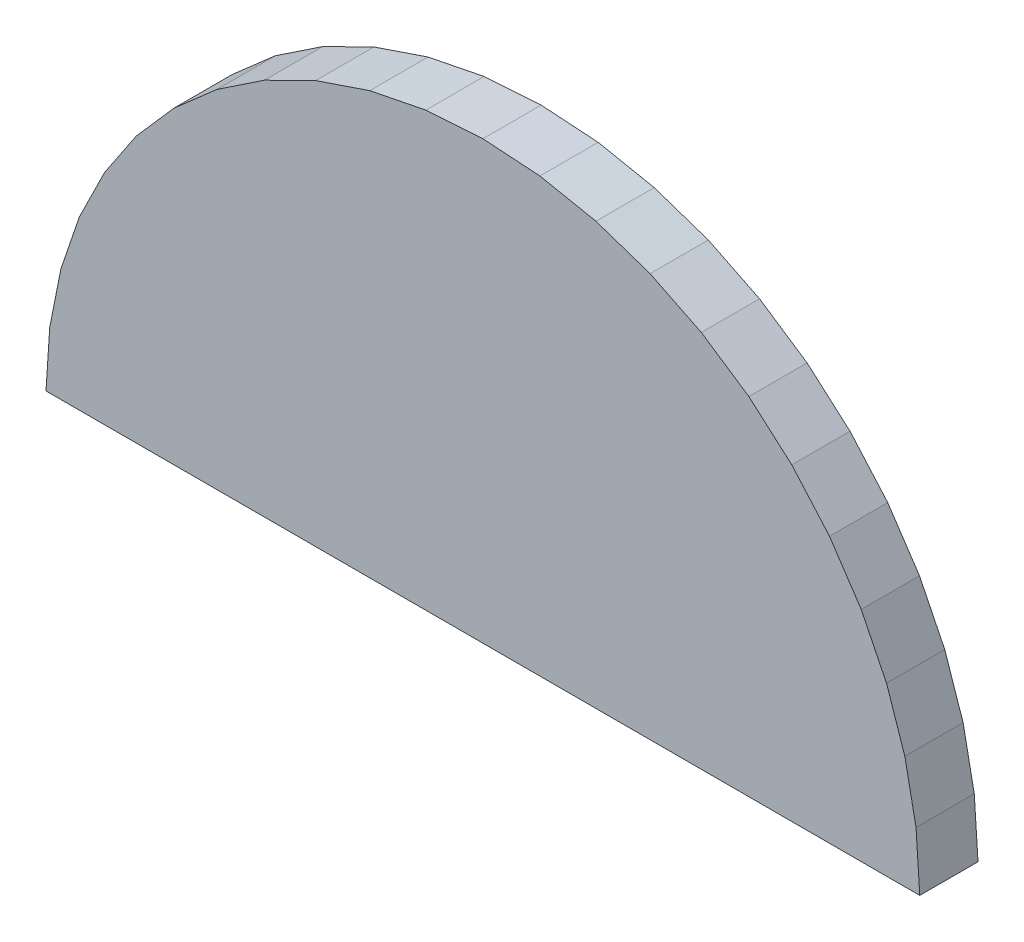
SolidWorks part; units mm, degrees
ref_plane "前视基准面" through (0, 0, 0) normal (0, 0, 1) x (1, 0, 0)
ref_plane "上视基准面" through (0, 0, 0) normal (0, 1, 0) x (1, 0, 0)
ref_plane "右视基准面" through (0, 0, 0) normal (1, 0, 0) x (0, 0, -1)
other "Configuration Table"
sketch "草图1" plane through (0, 0, 0) normal (0, 0, 1) x (1, 0, 0)
  line L0 (90, 0) -> (89.23, 11.7474)
  line L1 (89.23, 11.7474) -> (86.9333, 23.2937)
  line L2 (86.9333, 23.2937) -> (83.1492, 34.4415)
  line L3 (83.1492, 34.4415) -> (77.9423, 45)
  line L4 (77.9423, 45) -> (71.4018, 54.7885)
  line L5 (71.4018, 54.7885) -> (63.6396, 63.6396)
  line L6 (63.6396, 63.6396) -> (54.7885, 71.4018)
  line L7 (54.7885, 71.4018) -> (45, 77.9423)
  line L8 (45, 77.9423) -> (34.4415, 83.1492)
  line L9 (34.4415, 83.1492) -> (23.2937, 86.9333)
  line L10 (23.2937, 86.9333) -> (11.7474, 89.23)
  line L11 (11.7474, 89.23) -> (0, 90)
  line L12 (0, 90) -> (-11.7474, 89.23)
  line L13 (-11.7474, 89.23) -> (-23.2937, 86.9333)
  line L14 (-23.2937, 86.9333) -> (-34.4415, 83.1492)
  line L15 (-34.4415, 83.1492) -> (-45, 77.9423)
  line L16 (-45, 77.9423) -> (-54.7885, 71.4018)
  line L17 (-54.7885, 71.4018) -> (-63.6396, 63.6396)
  line L18 (-63.6396, 63.6396) -> (-71.4018, 54.7885)
  line L19 (-71.4018, 54.7885) -> (-77.9423, 45)
  line L20 (-77.9423, 45) -> (-83.1492, 34.4415)
  line L21 (-83.1492, 34.4415) -> (-86.9333, 23.2937)
  line L22 (-86.9333, 23.2937) -> (-89.23, 11.7474)
  line L23 (-89.23, 11.7474) -> (-90, 0)
  line L24 (-90, 0) -> (90, 0)
  dimension "x0" = 90
  dimension "x1" = 89.23
  dimension "x2" = 86.9333
  dimension "x3" = 83.1492
  dimension "x4" = 77.9423
  dimension "x5" = 71.4018
  dimension "x6" = 63.6396
  dimension "x7" = 54.7885
  dimension "x8" = 45
  dimension "x9" = 34.4415
  dimension "x10" = 23.2937
  dimension "x11" = 11.7474
  dimension "x13" = 11.7474
  dimension "x14" = 23.2937
  dimension "x15" = 34.4415
  dimension "x16" = 45
  dimension "x17" = 54.7885
  dimension "x18" = 63.6396
  dimension "x19" = 71.4018
  dimension "x20" = 77.9423
  dimension "x21" = 83.1492
  dimension "x22" = 86.9333
  dimension "x23" = 89.23
  dimension "x24" = 90
  dimension "y1" = 11.7474
  dimension "y2" = 23.2937
  dimension "y3" = 34.4415
  dimension "y4" = 45
  dimension "y5" = 54.7885
  dimension "y6" = 63.6396
  dimension "y7" = 71.4018
  dimension "y8" = 77.9423
  dimension "y9" = 83.1492
  dimension "y10" = 86.9333
  dimension "y11" = 89.23
  dimension "y12" = 90
  dimension "y13" = 89.23
  dimension "y14" = 86.9333
  dimension "y15" = 83.1492
  dimension "y16" = 77.9423
  dimension "y17" = 71.4018
  dimension "y18" = 63.6396
  dimension "y19" = 54.7885
  dimension "y20" = 45
  dimension "y21" = 34.4415
  dimension "y22" = 23.2937
  dimension "y23" = 11.7474
extrude "Semicircular_camera_platform" add sketch "草图1" along normal blind 12
